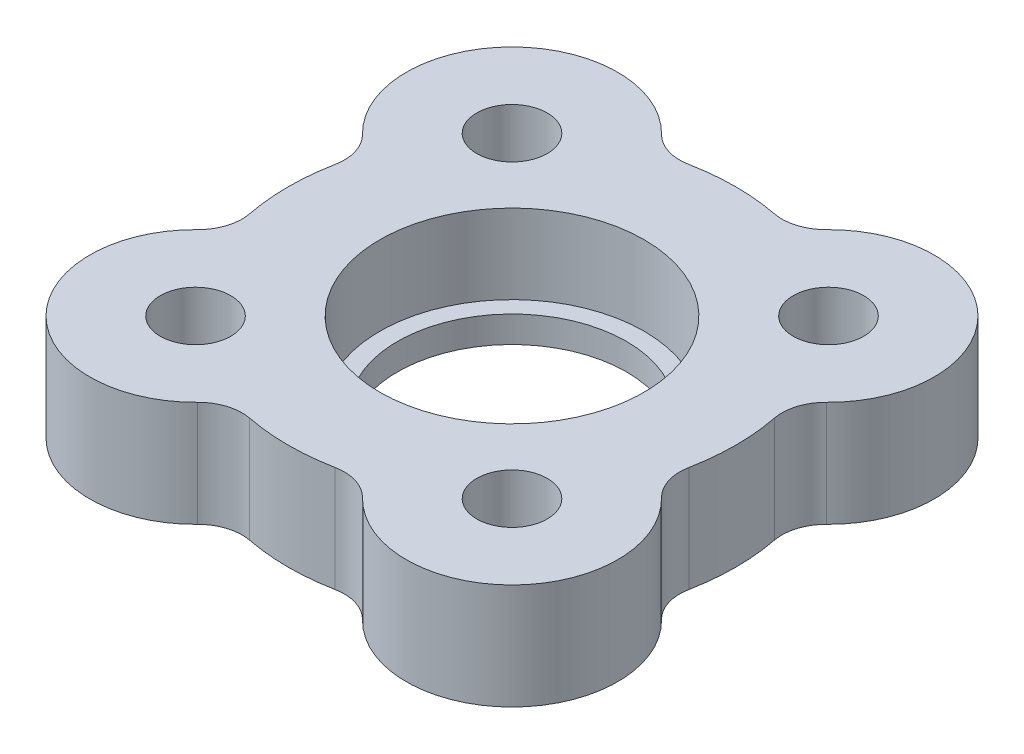
SolidWorks part; units mm, degrees
material "1060 Alloy"
ref_plane "Front" through (0, 0, 0) normal (0, 0, 1) x (1, 0, 0)
ref_plane "Top" through (0, 0, 0) normal (0, 1, 0) x (1, 0, 0)
ref_plane "Right" through (0, 0, 0) normal (1, 0, 0) x (0, 0, -1)
sketch "Sketch1" plane through (0, 0, 0) normal (0, 1, 0) x (1, 0, 0)
  circle A0 centre (-17.9605, 17.9605) radius 4
  circle A1 centre (17.9605, 17.9605) radius 4
  circle A2 centre (17.9605, -17.9605) radius 4
  circle A3 centre (-17.9605, -17.9605) radius 4
  circle A4 centre (0, 0) radius 13
  arc A5 (-9.3775, 26.347) -> (-26.347, 9.3775) centre (-17.9605, 17.9605) ccw
  arc A6 (26.347, 9.3775) -> (9.3775, 26.347) centre (17.9605, 17.9605) ccw
  arc A7 (9.3775, -26.347) -> (26.347, -9.3775) centre (17.9605, -17.9605) ccw
  arc A8 (-26.347, -9.3775) -> (-9.3775, -26.347) centre (-17.9605, -17.9605) ccw
  arc A9 (-24.9332, 4.8471) -> (-24.9332, -4.8471) centre (0, 0) ccw
  arc A10 (-4.8471, -24.9332) -> (4.8471, -24.9332) centre (0, 0) ccw
  arc A11 (24.9332, -4.8471) -> (24.9332, 4.8471) centre (0, 0) ccw
  arc A12 (-4.8471, 24.9332) -> (-9.3775, 26.347) centre (-5.8013, 29.8413) cw
  arc A13 (4.8471, 24.9332) -> (-4.8471, 24.9332) centre (0, 0) ccw
  arc A14 (9.3775, 26.347) -> (4.8471, 24.9332) centre (5.8013, 29.8413) cw
  arc A15 (26.347, 9.3775) -> (24.9332, 4.8471) centre (29.8413, 5.8013) ccw
  arc A16 (24.9332, -4.8471) -> (26.347, -9.3775) centre (29.8413, -5.8013) ccw
  arc A17 (9.3775, -26.347) -> (4.8471, -24.9332) centre (5.8013, -29.8413) ccw
  arc A18 (-4.8471, -24.9332) -> (-9.3775, -26.347) centre (-5.8013, -29.8413) ccw
  arc A19 (-24.9332, -4.8471) -> (-26.347, -9.3775) centre (-29.8413, -5.8013) cw
  arc A20 (-24.9332, 4.8471) -> (-26.347, 9.3775) centre (-29.8413, 5.8013) ccw
  point P0 (0, 0)
  point P17 (0, 0)
  point P27 (0, 0)
  dimension "D5" = 8
  dimension "D6" = 26
  dimension "D1" = 5
  dimension "D3" = 25.4
  dimension "D4" = 4
  dimension "D8" = 4
extrude "body and main holes" add sketch "Sketch1" along normal blind 12
sketch "Sketch3" plane through (0, 12, 0) normal (0, -1, 0) x (1, 0, 0)
  circle A0 centre (0, 0) radius 15
  dimension "D1" = 30
extrude "bearing hole" cut sketch "Sketch3" along normal blind 9
sketch "Sketch4" plane through (0, 12, 0) normal (0, 1, 0) x (1, 0, 0)
  line L0 (-17.9605, 17.9605) -> (17.9605, -17.9605) construction
sketch "Sketch5" plane through (0, 0, 0) normal (0, -1, 0) x (1, 0, 0)
  line L0 (-17.9605, -17.9605) -> (17.9605, 17.9605) construction
equation "\"D3@Sketch1\"=\"square plate bolt pattern diameter\"/2"
equation "\"D1@body and main holes\"=\"bearing plate thickness\""
equation "\"D1@Sketch3\" = \"bearing OD\""
equation "\"D1@bearing hole\" = \"bearing depth\""
equation "\"D5@Sketch1\"=\"square plate bolt hole ID\""
equation "\"D6@Sketch1\"=\"bearing plate bearing stop ID\""
equation "\"bearing OD\" = 30mm"
equation "\"bearing outer race thickness\"= 1mm"
equation "\"bearing ID\"= 10mm"
equation "\"bearing depth\"= 9mm"
equation "\"bearing inner race thickness\"= 1mm"
equation "\"small seal OD\" = 20mm"
equation "\"small seal ID\"= 8mm"
equation "\"small seal depth\" = 6mm"
equation "\"big seal OD\" = 30mm"
equation "\"big seal ID\"= 15mm"
equation "\"big seal depth\"= 8mm"
equation "\"z\" = 12"
equation "\"de\" = 0.426in"
equation "\"d2\" = 2.097in"
equation "\"d_exit\" =\"b2\""
equation "\"theta\" = 15"
equation "\"b2\" = .15in"
equation "\"b1\" = \"b2\" + (\"d2\"/2 - \"de\"/2)*sin(\"theta\")"
equation "\"s\" = ( 1/\"z\")*(3.14*\"de\" - (3.14*(\"de\"^2) / (4*(\"b1\"))))"
equation "\"s_opening\" = (3.14*\"de\" - \"z\"*\"s\")/\"z\""
equation "\"area_eye\"=3.14*(\"de\"^2)/4"
equation "\"single_channel_area\"=\"s_opening\"*\"b1\""
equation "\"impeller upper clearance\"= .5mm"
equation "\"impeller horizontal clearance\"= .5mm"
equation "\"impeller bottom clearance\"= .5mm"
equation "\"impeller base thickness\"= 2mm"
equation "\"impeller boss depth\" = 14mm"
equation "\"impeller boss diameter\" = \"big seal ID\""
equation "\"impeller dowel diameter\" = 2mm"
equation "\"impeller bolt head diameter\" = 7.5mm"
equation "\"impeller bolt head depth\" = 4mm"
equation "\"impeller shaft bore\"= 8mm"
equation "\"impeller shaft bore depth\" = \"impeller boss depth\" + \"impeller base thickness\" - \"impeller bolt head depth\" - 3mm"
equation "\"impeller dowel length\" = 2mm*2 + \"impeller shaft bore\""
equation "\"impeller screw hole bore\" = 4mm"
equation "\"shaft impeller screw hole diameter\" = \"impeller screw hole bore\""
equation "\"shaft impeller section length\" = \"impeller shaft bore depth\""
equation "\"shaft impeller screw hole depth\" = \"shaft impeller section length\"-\"impeller dowel diameter\"-2mm"
equation "\"shaft impeller section diameter\" = \"impeller shaft bore\""
equation "\"shaft seal section diameter\"=\"small seal ID\""
equation "\"shaft seal section length\"=\"small seal depth\" + 2mm"
equation "\"shaft bearing section diameter\" = \"bearing ID\""
equation "\"shaft bearing section length\" = \"bearing depth\""
equation "\"shaft bearing stop diameter\" = \"bearing ID\" + 2mm"
equation "\"shaft bearing stop length\" = 2mm"
equation "\"shaft coupler section diameter\" = 8mm"
equation "\"shaft coupler section length\" = \"shaft bearing stop length\" + \"coupler length\"/2 + 4mm"
equation "\"coupler set screw drill hole ID\"= 6mm"
equation "\"coupler set screw 1 distance\"= \"motor mount shaft hole depth\" / 3"
equation "\"coupler set screw 2 distance\"= \"motor mount shaft hole depth\" * 4 / 5"
equation "\"coupler motor shaft hole ID\"= 8mm"
equation "\"coupler impeller shaft hole ID\"= \"shaft coupler section diameter\""
equation "\"coupler OD\"= 17mm"
equation "\"coupler length\"= 25mm"
equation "\"square plate diameter\" = 3in"
equation "\"square plate bolt pattern diameter\"= 2in"
equation "\"square plate bolt hole ID\" = 8mm"
equation "\"bearing plate bearing stop ID\" = \"bearing OD\" - 4mm"
equation "\"bearing plate bearing stop depth\" = 3mm"
equation "\"bearing plate thickness\" = \"bearing depth\" + \"bearing plate bearing stop depth\""
equation "\"small seal plate lip depth\" = \"shaft bearing stop length\" + 1mm"
equation "\"small seal plate lip ID\" = \"small seal OD\" - 3mm"
equation "\"small seal plate thickness\" = \"small seal plate lip depth\" + \"small seal depth\""
equation "\"big seal plate lip depth\" = 3mm"
equation "\"big seal plate thickness\" = \"shaft bearing stop length\" + \"shaft seal section length\" + \"impeller boss depth\" - \"impeller bottom clearance\"-\"small seal plate thickness\""
equation "\"impeller cavity center height\"= \"impeller bottom clearance\" + \"impeller upper clearance\" + \"final impeller center height\""
equation "\"impeller cavity diameter\"= 2 * \"impeller horizontal clearance\" + \"d2\""
equation "\"impeller cavity outer height\"= \"impeller bottom clearance\" + \"impeller upper clearance\" + \"impeller base thickness\" + \"b2\""
equation "\"impeller housing bolt count\" = 8"
equation "\"impeller housing bolt diameter\" = 6mm"
equation "\"impeller housing bolt pattern diameter\" = 2.75in"
equation "\"impeller housing o-ring channel height\"= 1.5mm"
equation "\"impeller housing o ring channel width\"= 1.5mm"
equation "\"impeller housing o-ring diameter\" = 2in"
equation "\"impeller housing threaded inlet diameter\" = 14mm"
equation "\"impeller housing threaded inlet depth\"= 8mm"
equation "\"impeller housing thickness\"= \"impeller housing threaded inlet depth\" + \"impeller cavity center height\"+ 4mm"
equation "\"impeller housing exit threaded diameter\"= 8mm"
equation "\"impeller housing exit threaded depth\"= 8mm"
equation "\"impeller housing diameter\" = 3.5in"
equation "\"impeller housing diffuser conical angle\"=10"
equation "\"impeller housing diffuser tangent angle\"=20"
equation "\"impeller housing outlet purchase\" = 5mm"
equation "\"motor to housing distance\" = \"motor shaft pride\" + \"shaft coupler section length\" - \"bearing plate bearing stop depth\" + 2mm"
equation "\"motor mount coupler hole diameter\"= \"coupler OD\"+ 4mm"
equation "\"motor mount to housing post radius\"= ( 3 * \"square plate bolt hole ID\" ) / 2"
equation "\"motor mount m4 screw hole diameter\"= 4mm"
equation "\"motor mount m4 head diameter\"= 7.25mm"
equation "\"motor mount m4 head depth\"= 4mm"
equation "\"motor mount plate thickness\"= 8mm + \"motor mount m4 head depth\""
equation "\"motor shaft pride\"= 32mm"
equation "\"motor shaft flat section length from tip\"= 25.7mm"
equation "\"motor shaft bore end clearance\"= 2mm"
equation "\"coupler shaft to motor clearance\" = 2mm"
equation "\"motor mount shaft hole depth\"= \"motor shaft pride\""
